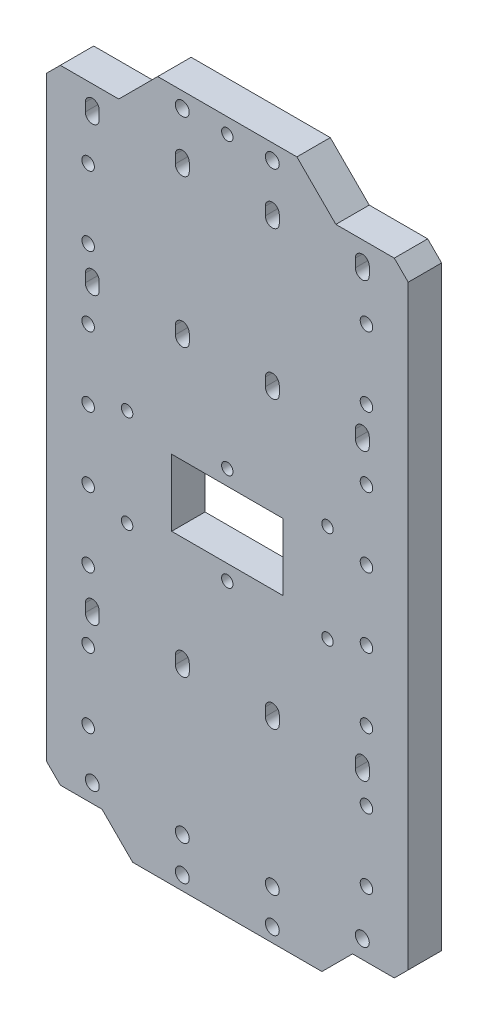
SolidWorks part; units mm, degrees
material "Beech"
ref_plane "Front Plane" through (0, 0, 0) normal (0, 0, 1) x (1, 0, 0)
ref_plane "Top Plane" through (0, 0, 0) normal (0, 1, 0) x (1, 0, 0)
ref_plane "Right Plane" through (0, 0, 0) normal (1, 0, 0) x (0, 0, -1)
sketch "Model" plane through (0, 0, 0) normal (0, 0, 1) x (1, 0, 0)
  line L0 (85, 110) -> (45, 110)
  line L1 (85, 134) -> (85, 110)
  line L2 (45, 134) -> (85, 134)
  line L3 (45, 110) -> (45, 134)
  line L4 (13.99, 174.82) -> (13.99, 171.82)
  line L5 (18.99, 171.82) -> (18.99, 174.82)
  line L6 (46.33, 174.82) -> (46.33, 171.82)
  line L7 (51.33, 171.82) -> (51.33, 174.82)
  line L8 (78.67, 174.82) -> (78.67, 171.82)
  line L9 (83.67, 171.82) -> (83.67, 174.82)
  line L10 (111.01, 174.82) -> (111.01, 171.82)
  line L11 (116.01, 171.82) -> (116.01, 174.82)
  line L12 (13.99, 228) -> (13.99, 225)
  line L13 (18.99, 225) -> (18.99, 228)
  line L14 (51.33, 225) -> (51.33, 228)
  line L15 (46.33, 228) -> (46.33, 225)
  line L16 (83.67, 225) -> (83.67, 228)
  line L17 (78.67, 228) -> (78.67, 225)
  line L18 (116.01, 225) -> (116.01, 228)
  line L19 (111.01, 228) -> (111.01, 225)
  line L20 (18.99, 69.18) -> (18.99, 72.18)
  line L21 (13.99, 72.18) -> (13.99, 69.18)
  line L22 (51.33, 69.18) -> (51.33, 72.18)
  line L23 (46.33, 72.18) -> (46.33, 69.18)
  line L24 (83.67, 69.18) -> (83.67, 72.18)
  line L25 (78.67, 72.18) -> (78.67, 69.18)
  line L26 (116.01, 69.18) -> (116.01, 72.18)
  line L27 (111.01, 72.18) -> (111.01, 69.18)
  line L28 (125, 11) -> (130, 16)
  line L29 (99, 0) -> (110, 11)
  line L30 (99, 0) -> (31, 0)
  line L31 (20, 11) -> (31, 0)
  line L32 (0, 16) -> (5, 11)
  line L33 (5, 235) -> (0, 230)
  line L34 (26, 235) -> (5, 235)
  line L35 (40, 249) -> (26, 235)
  line L36 (40, 249) -> (90, 249)
  line L37 (104, 235) -> (90, 249)
  line L38 (125, 235) -> (104, 235)
  line L39 (130, 230) -> (125, 235)
  line L40 (0, 230) -> (0, 16)
  line L41 (130, 16) -> (130, 230)
  line L42 (110, 11) -> (125, 11)
  line L43 (5, 11) -> (20, 11)
  line L44 (16.49, 228) -> (16.49, 171.82) construction
  line L45 (15, 59.5) -> (115, 59.5) construction
  line L46 (15, 59.5) -> (15, 34.5) construction
  line L47 (15, 34.5) -> (115, 34.5) construction
  line L48 (115, 59.5) -> (115, 34.5) construction
  line L49 (15, 84.5) -> (115, 84.5) construction
  line L50 (15, 84.5) -> (15, 59.5) construction
  line L51 (15, 59.5) -> (115, 59.5) construction
  line L52 (115, 84.5) -> (115, 59.5) construction
  line L53 (15, 109.5) -> (115, 109.5) construction
  line L54 (15, 109.5) -> (15, 84.5) construction
  line L55 (15, 84.5) -> (115, 84.5) construction
  line L56 (115, 109.5) -> (115, 84.5) construction
  line L57 (15, 134.5) -> (115, 134.5) construction
  line L58 (15, 134.5) -> (15, 109.5) construction
  line L59 (15, 109.5) -> (115, 109.5) construction
  line L60 (115, 134.5) -> (115, 109.5) construction
  line L61 (15, 159.5) -> (115, 159.5) construction
  line L62 (15, 159.5) -> (15, 134.5) construction
  line L63 (15, 134.5) -> (115, 134.5) construction
  line L64 (115, 159.5) -> (115, 134.5) construction
  line L65 (15, 184.5) -> (115, 184.5) construction
  line L66 (15, 184.5) -> (15, 159.5) construction
  line L67 (15, 159.5) -> (115, 159.5) construction
  line L68 (115, 184.5) -> (115, 159.5) construction
  line L69 (15, 209.5) -> (115, 209.5) construction
  line L70 (15, 209.5) -> (15, 184.5) construction
  line L71 (15, 184.5) -> (115, 184.5) construction
  line L72 (115, 209.5) -> (115, 184.5) construction
  line L73 (16.49, 171.82) -> (113.51, 171.82) construction
  line L74 (113.51, 171.82) -> (113.51, 228) construction
  line L75 (113.51, 228) -> (16.49, 228) construction
  line L76 (48.83, 243.5) -> (81.17, 243.5) construction
  line L77 (16.49, 225) -> (113.51, 225) construction
  line L78 (16.49, 174.82) -> (113.51, 174.82) construction
  line L79 (16.49, 17.5) -> (113.51, 17.5) construction
  line L80 (29, 139.5) -> (101, 139.5) construction
  line L81 (29, 139.5) -> (29, 104.5) construction
  line L82 (29, 104.5) -> (101, 104.5) construction
  line L83 (101, 139.5) -> (101, 104.5) construction
  line L84 (48.83, 17.5) -> (48.83, 5) construction
  line L85 (81.17, 17.5) -> (81.17, 5) construction
  line L86 (81.17, 5) -> (48.83, 5) construction
  line L87 (16.49, 72.18) -> (16.49, 17.5) construction
  line L88 (16.49, 72.18) -> (113.51, 72.18) construction
  line L89 (113.51, 72.18) -> (113.51, 17.5) construction
  line L90 (16.49, 69.18) -> (113.51, 69.18) construction
  line L91 (48.83, 72.18) -> (48.83, 17.5) construction
  line L92 (81.17, 72.18) -> (81.17, 17.5) construction
  line L93 (16.49, 171.82) -> (16.49, 72.18) construction
  line L94 (48.83, 171.82) -> (48.83, 72.18) construction
  line L95 (81.17, 171.82) -> (81.17, 72.18) construction
  line L96 (113.51, 171.82) -> (113.51, 72.18) construction
  line L97 (48.83, 228) -> (48.83, 174.82) construction
  line L98 (81.17, 228) -> (81.17, 174.82) construction
  line L99 (48.83, 228) -> (48.83, 243.5) construction
  line L100 (81.17, 243.5) -> (81.17, 228) construction
  line L101 (0, 16) -> (0, 0) construction
  line L102 (31, 0) -> (0, 0) construction
  circle A0 centre (16.49, 17.5) radius 2.5
  circle A1 centre (48.83, 17.5) radius 2.5
  circle A2 centre (81.17, 17.5) radius 2.5
  circle A3 centre (113.51, 17.5) radius 2.5
  circle A4 centre (29, 139.5) radius 2.05
  circle A5 centre (65, 139.5) radius 2.05
  circle A6 centre (101, 139.5) radius 2.05
  circle A7 centre (101, 104.5) radius 2.05
  circle A8 centre (65, 104.5) radius 2.05
  circle A9 centre (29, 104.5) radius 2.05
  circle A10 centre (65, 243.5) radius 2.05
  circle A11 centre (81.17, 5) radius 2.5
  circle A12 centre (48.83, 5) radius 2.5
  circle A13 centre (81.17, 243.5) radius 2.5
  circle A14 centre (48.83, 243.5) radius 2.5
  circle A15 centre (115, 34.5) radius 2.25
  circle A16 centre (115, 59.5) radius 2.25
  circle A17 centre (15, 34.5) radius 2.25
  circle A18 centre (15, 59.5) radius 2.25
  circle A19 centre (15, 84.5) radius 2.25
  circle A20 centre (15, 109.5) radius 2.25
  circle A21 centre (115, 84.5) radius 2.25
  circle A22 centre (115, 109.5) radius 2.25
  circle A23 centre (115, 134.5) radius 2.25
  circle A24 centre (15, 134.5) radius 2.25
  circle A25 centre (15, 159.5) radius 2.25
  circle A26 centre (115, 159.5) radius 2.25
  circle A27 centre (115, 184.5) radius 2.25
  circle A28 centre (15, 184.5) radius 2.25
  circle A29 centre (15, 209.5) radius 2.25
  circle A30 centre (115, 209.5) radius 2.25
  arc A31 (13.99, 171.82) -> (18.99, 171.82) centre (16.49, 171.82) ccw
  arc A32 (18.99, 174.82) -> (13.99, 174.82) centre (16.49, 174.82) ccw
  arc A33 (46.33, 171.82) -> (51.33, 171.82) centre (48.83, 171.82) ccw
  arc A34 (51.33, 174.82) -> (46.33, 174.82) centre (48.83, 174.82) ccw
  arc A35 (78.67, 171.82) -> (83.67, 171.82) centre (81.17, 171.82) ccw
  arc A36 (83.67, 174.82) -> (78.67, 174.82) centre (81.17, 174.82) ccw
  arc A37 (111.01, 171.82) -> (116.01, 171.82) centre (113.51, 171.82) ccw
  arc A38 (116.01, 174.82) -> (111.01, 174.82) centre (113.51, 174.82) ccw
  arc A39 (13.99, 225) -> (18.99, 225) centre (16.49, 225) ccw
  arc A40 (18.99, 228) -> (13.99, 228) centre (16.49, 228) ccw
  arc A41 (46.33, 225) -> (51.33, 225) centre (48.83, 225) ccw
  arc A42 (51.33, 228) -> (46.33, 228) centre (48.83, 228) ccw
  arc A43 (78.67, 225) -> (83.67, 225) centre (81.17, 225) ccw
  arc A44 (83.67, 228) -> (78.67, 228) centre (81.17, 228) ccw
  arc A45 (111.01, 225) -> (116.01, 225) centre (113.51, 225) ccw
  arc A46 (116.01, 228) -> (111.01, 228) centre (113.51, 228) ccw
  arc A47 (13.99, 69.18) -> (18.99, 69.18) centre (16.49, 69.18) ccw
  arc A48 (18.99, 72.18) -> (13.99, 72.18) centre (16.49, 72.18) ccw
  arc A49 (46.33, 69.18) -> (51.33, 69.18) centre (48.83, 69.18) ccw
  arc A50 (51.33, 72.18) -> (46.33, 72.18) centre (48.83, 72.18) ccw
  arc A51 (78.67, 69.18) -> (83.67, 69.18) centre (81.17, 69.18) ccw
  arc A52 (83.67, 72.18) -> (78.67, 72.18) centre (81.17, 72.18) ccw
  arc A53 (111.01, 69.18) -> (116.01, 69.18) centre (113.51, 69.18) ccw
  arc A54 (116.01, 72.18) -> (111.01, 72.18) centre (113.51, 72.18) ccw
  dimension "D34" = 5
  dimension "D35" = 4.1
  dimension "D36" = 4.5
  dimension "D37" = 40
  dimension "D1" = 54.68
  dimension "D2" = 12.5
  dimension "D3" = 3
  dimension "D4" = 25
  dimension "D5" = 25
  dimension "D6" = 25
  dimension "D7" = 25
  dimension "D8" = 25
  dimension "D9" = 25
  dimension "D10" = 25
  dimension "D11" = 102.64
  dimension "D12" = 53.18
  dimension "D13" = 32.34
  dimension "D14" = 32.34
  dimension "D15" = 32.34
  dimension "D16" = 5
  dimension "D17" = 11
  dimension "D18" = 34.5
  dimension "D19" = 15
  dimension "D20" = 100
  dimension "D21" = 29
  dimension "D22" = 72
  dimension "D23" = 45
  dimension "D24" = 24
  dimension "D25" = 35
  dimension "D26" = 5.5
  dimension "D27" = 93.5
  dimension "D28" = 235
  dimension "D29" = 249
  dimension "D30" = 130
  dimension "D31" = 14
  dimension "D32" = 26
  dimension "D33" = 50
  dimension "D38" = 5
  dimension "D39" = 5
  dimension "D40" = 5
  dimension "D41" = 20
  dimension "D42" = 11
  dimension "D43" = 16.49
  dimension "D44" = 5.5
extrude "Boss-Extrude1" add sketch "Model" along normal blind 12
